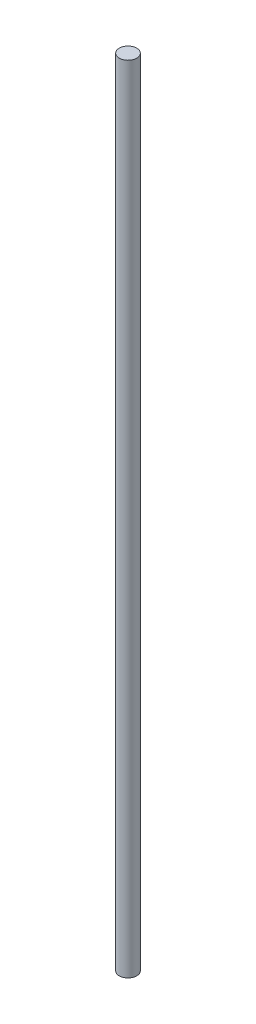
SolidWorks part; units mm, degrees
material "Alloy Steel"
ref_plane "Front Plane" through (0, 0, 0) normal (0, 0, 1) x (1, 0, 0)
ref_plane "Top Plane" through (0, 0, 0) normal (0, 1, 0) x (1, 0, 0)
ref_plane "Right Plane" through (0, 0, 0) normal (1, 0, 0) x (0, 0, -1)
sketch "Sketch1" plane through (0, 0, 0) normal (0, 1, 0) x (1, 0, 0)
  circle A0 centre (0, 0) radius 3.175
  dimension "D1" = 6.35
extrude "Boss-Extrude1" add sketch "Sketch1" along normal blind 288.925
equation "\"airframeInnerDiameter\"= 6in"
equation "\"outerDiameter\"= 6.112in"
equation "\"airframeThickness\" = .056in"
equation "\"airframeBulkheadThickness\"= 0.125in"
equation "\"payloadAirframeLength\"= 10in"
equation "\"payloadInnerDiameter\"= 6in - \"airframeThickness\""
equation "\"payloadOuterDiameter\"= \"airframeInnerDiameter\""
equation "\"totalPayloadLength\" = 12in"
equation "\"strutWidth\" = 0.5in"
equation "\"rodDiameter\" = 0.25in"
equation "\"rodSeperation\" = 1.625in"
equation "\"plateThickness\" = .375in"
equation "\"D1@Sketch1\"=\"rodDiameter\""
